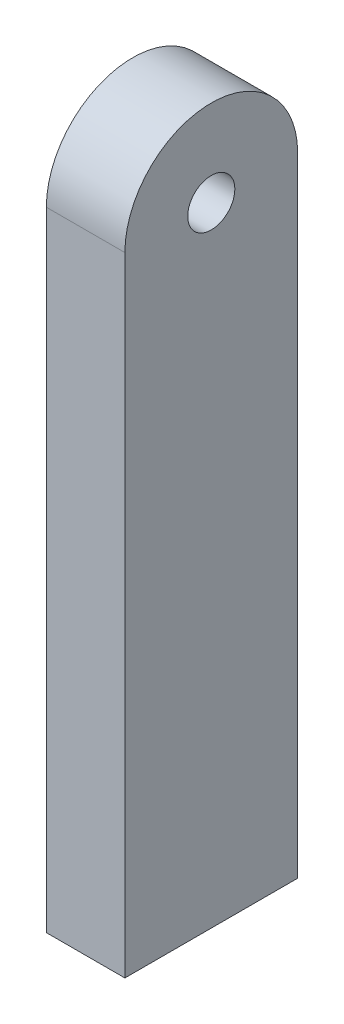
SolidWorks part; units mm, degrees
ref_plane "Front" through (0, 0, 0) normal (0, 0, 1) x (1, 0, 0)
ref_plane "Top" through (0, 0, 0) normal (0, 1, 0) x (1, 0, 0)
ref_plane "Right" through (0, 0, 0) normal (1, 0, 0) x (0, 0, -1)
sketch "Sketch1" plane through (0, 0, 0) normal (1, 0, 0) x (0, 0, -1)
  line L0 (0, 20) -> (0, -20) construction
  line L1 (-5.5, 20) -> (-5.5, -20)
  line L2 (5.5, 20) -> (5.5, -20)
  line L5 (-5.5, -20) -> (5.5, -20)
  circle A0 centre (0, 20) radius 1.5
  arc A6 (5.5, 20) -> (-5.5, 20) centre (0, 20) ccw
  point P3 (0, 0)
  point P10 (0, 0)
  dimension "D4" = 3
  dimension "D2" = 4
  dimension "D1" = 40
extrude "Boss-Extrude1" add sketch "Sketch1" along normal blind 5
sketch "Sketch2" plane through (0, -20, 0) normal (0, -1, 0) x (1, 0, 0)
  line L0 (2.5, 5.5) -> (2.5, -5.5) construction
  line L4 (5, 5.5) -> (0, 5.5) construction
  circle A0 centre (2.5, 0) radius 2
  point P2 (0, 0)
  point P4 (0, 0)
  point P8 (0, 0)
  point P12 (2.5, -3.7749)
  point P13 (2.5, 5.5)
  dimension "D1" = 4
extrude "Cut-Extrude1" cut sketch "Sketch2" against normal offset from surface (33.8153 mm away) 5 contours A0
